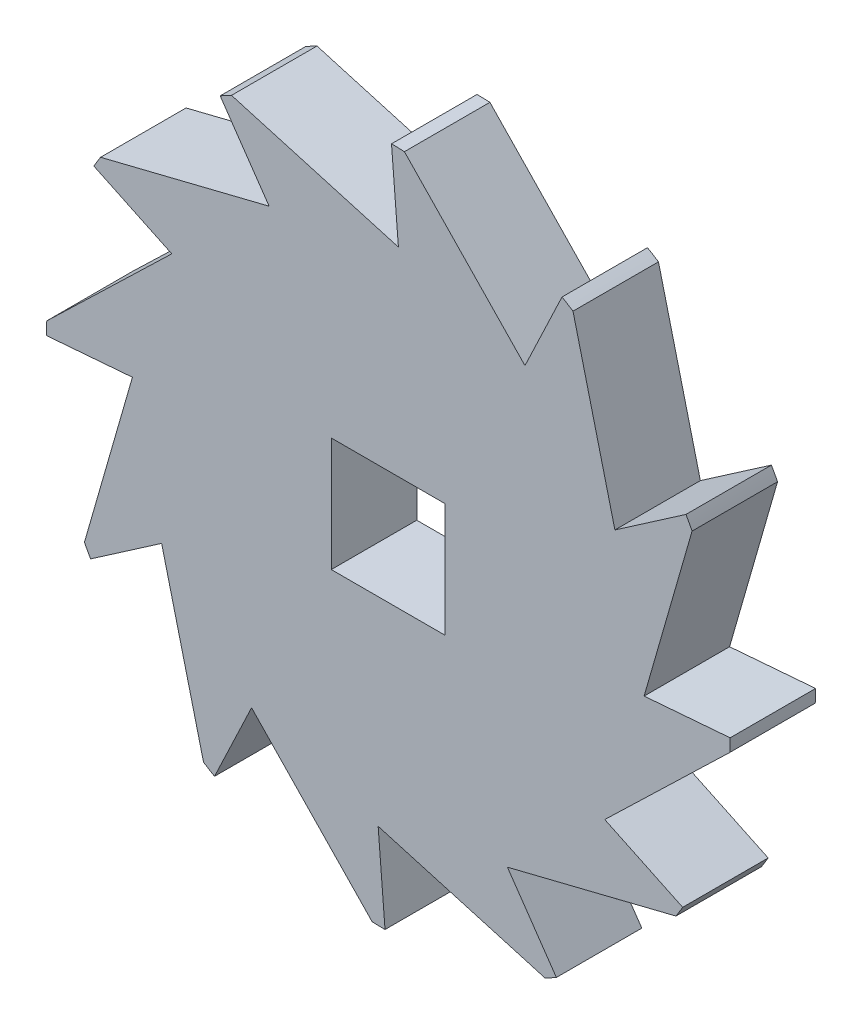
SolidWorks part; units mm, degrees
ref_plane "Piano frontale" through (0, 0, 0) normal (0, 0, 1) x (1, 0, 0)
ref_plane "Piano superiore" through (0, 0, 0) normal (0, 1, 0) x (1, 0, 0)
ref_plane "Piano destro" through (0, 0, 0) normal (1, 0, 0) x (0, 0, -1)
sketch "Schizzo2" plane through (0, 0, 0) normal (0, 0, 1) x (1, 0, 0)
  circle A0 centre (0, 0) radius 30
  dimension "D1" = 60
extrude "Estrusione-Estrusione1" add sketch "Schizzo2" along normal blind 7.5
sketch "Schizzo3" plane through (0, 0, 0) normal (0, 0, -1) x (-1, 0, 0)
  line L1 (5, -5) -> (-5, -5)
  line L2 (5, -5) -> (5, 5)
  line L3 (5, 5) -> (-5, 5)
  line L4 (-5, -5) -> (-5, 5)
  line L5 (5, -5) -> (-5, 5) construction
  line L6 (5, 5) -> (-5, -5) construction
  point P0 (0, 0)
  dimension "D1" = 10
  dimension "D2" = 10
extrude "Taglio-Estrusione1" cut sketch "Schizzo3" against normal through all
sketch "Schizzo4" plane through (0, 0, 0) normal (0, 0, -1) x (-1, 0, 0)
  line L0 (-0.2853, 29.9986) -> (-0.89, 22.45)
  line L1 (-0.89, 22.45) -> (13.7555, 26.6606)
  line L2 (-5, 5) -> (-5, 29.5804) construction
  line L3 (5, 5) -> (-5, 5) construction
  line L4 (10.4542, 19.8873) -> (25.2429, 16.211)
  line L5 (14.7522, 26.1222) -> (10.4542, 19.8873)
  line L6 (18.9973, 11.9958) -> (29.9665, 1.4177)
  line L7 (25.8369, 15.2464) -> (18.9973, 11.9958)
  line L8 (22.45, 0.89) -> (26.6606, -13.7555)
  line L9 (29.9986, 0.2853) -> (22.45, 0.89)
  line L10 (19.8873, -10.4542) -> (16.211, -25.2429)
  line L11 (26.1222, -14.7522) -> (19.8873, -10.4542)
  line L12 (11.9958, -18.9973) -> (1.4177, -29.9665)
  line L13 (15.2464, -25.8369) -> (11.9958, -18.9973)
  line L14 (0.89, -22.45) -> (-13.7555, -26.6606)
  line L15 (0.2853, -29.9986) -> (0.89, -22.45)
  line L16 (-10.4542, -19.8873) -> (-25.2429, -16.211)
  line L17 (-14.7522, -26.1222) -> (-10.4542, -19.8873)
  line L18 (-18.9973, -11.9958) -> (-29.9665, -1.4177)
  line L19 (-25.8369, -15.2464) -> (-18.9973, -11.9958)
  line L20 (-22.45, -0.89) -> (-26.6606, 13.7555)
  line L21 (-29.9986, -0.2853) -> (-22.45, -0.89)
  line L22 (-19.8873, 10.4542) -> (-16.211, 25.2429)
  line L23 (-26.1222, 14.7522) -> (-19.8873, 10.4542)
  line L24 (-11.9958, 18.9973) -> (-1.4177, 29.9665)
  line L25 (-15.2464, 25.8369) -> (-11.9958, 18.9973)
  circle A0 centre (0, 0) radius 30 construction
  arc A1 (-16.211, 25.2429) -> (-26.1222, 14.7522) centre (0, 0) ccw
  arc A2 (-1.4177, 29.9665) -> (-15.2464, 25.8369) centre (0, 0) ccw
  arc A3 (13.7555, 26.6606) -> (-0.2853, 29.9986) centre (0, 0) ccw
  arc A4 (25.2429, 16.211) -> (14.7522, 26.1222) centre (0, 0) ccw
  arc A5 (29.9665, 1.4177) -> (25.8369, 15.2464) centre (0, 0) ccw
  arc A6 (26.6606, -13.7555) -> (29.9986, 0.2853) centre (0, 0) ccw
  arc A7 (16.211, -25.2429) -> (26.1222, -14.7522) centre (0, 0) ccw
  arc A8 (1.4177, -29.9665) -> (15.2464, -25.8369) centre (0, 0) ccw
  arc A9 (-13.7555, -26.6606) -> (0.2853, -29.9986) centre (0, 0) ccw
  arc A10 (-25.2429, -16.211) -> (-14.7522, -26.1222) centre (0, 0) ccw
  arc A11 (-29.9665, -1.4177) -> (-25.8369, -15.2464) centre (0, 0) ccw
  arc A12 (-26.6606, 13.7555) -> (-29.9986, -0.2853) centre (0, 0) ccw
  point P0 (0.7488, 22.45)
  dimension "D1" = 4.58
  dimension "D2" = 69.38
  dimension "D3" = 17.45
  dimension "D4" = 4.11
  dimension "D5" = 12
extrude "Taglio-Estrusione2" cut sketch "Schizzo4" against normal through all
